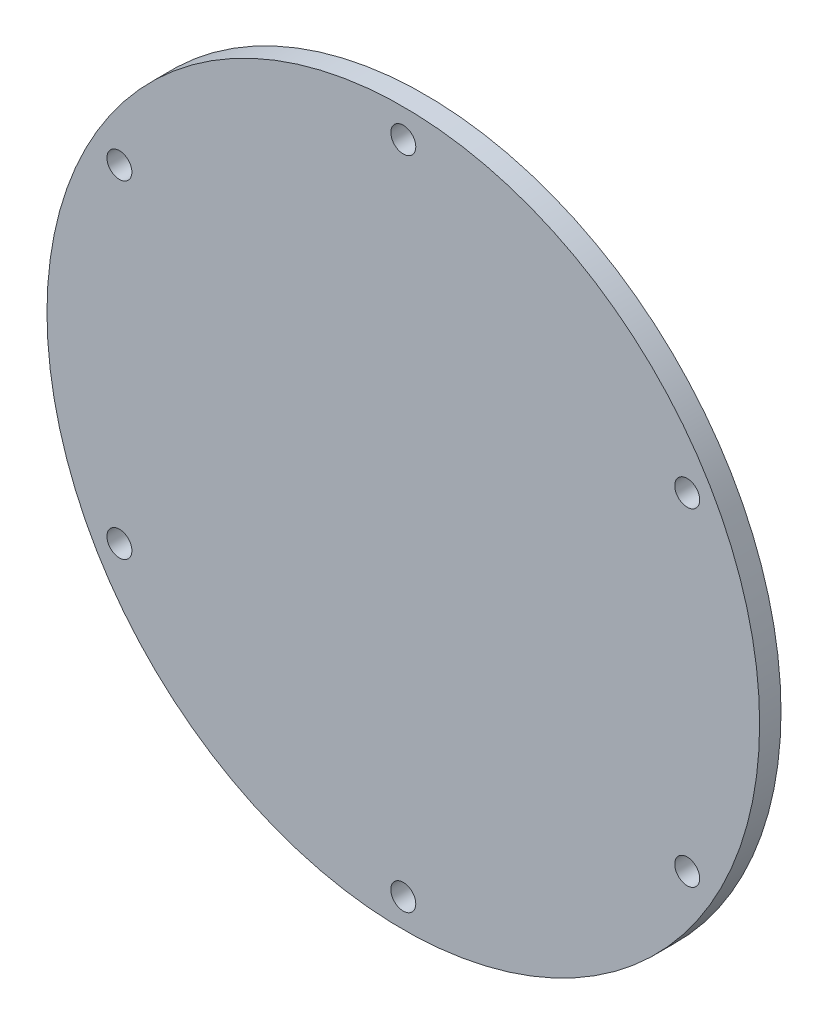
SolidWorks part; units mm, degrees
material "ABS"
ref_plane "Спереди" through (0, 0, 0) normal (0, 0, 1) x (1, 0, 0)
ref_plane "Сверху" through (0, 0, 0) normal (0, 1, 0) x (1, 0, 0)
ref_plane "Справа" through (0, 0, 0) normal (1, 0, 0) x (0, 0, -1)
sketch "Эскиз1" plane through (0, 0, 0) normal (0, 0, 1) x (1, 0, 0)
  line L0 (0, 0) -> (0, 50) construction
  circle A0 centre (0, 0) radius 50
  circle A2 centre (0, 46) radius 1.75
  circle A3 centre (39.8372, 23) radius 1.75
  circle A4 centre (39.8372, -23) radius 1.75
  circle A5 centre (0, -46) radius 1.75
  circle A6 centre (-39.8372, -23) radius 1.75
  circle A7 centre (-39.8372, 23) radius 1.75
  point P7 (40.1835, 14.2675)
  point P8 (0, 0)
  point P18 (0, 0)
  dimension "D1" = 100
  dimension "D2" = 3.5
  dimension "D3" = 4
  dimension "D4" = 6
extrude "Бобышка-Вытянуть1" add sketch "Эскиз1" along normal blind 3
